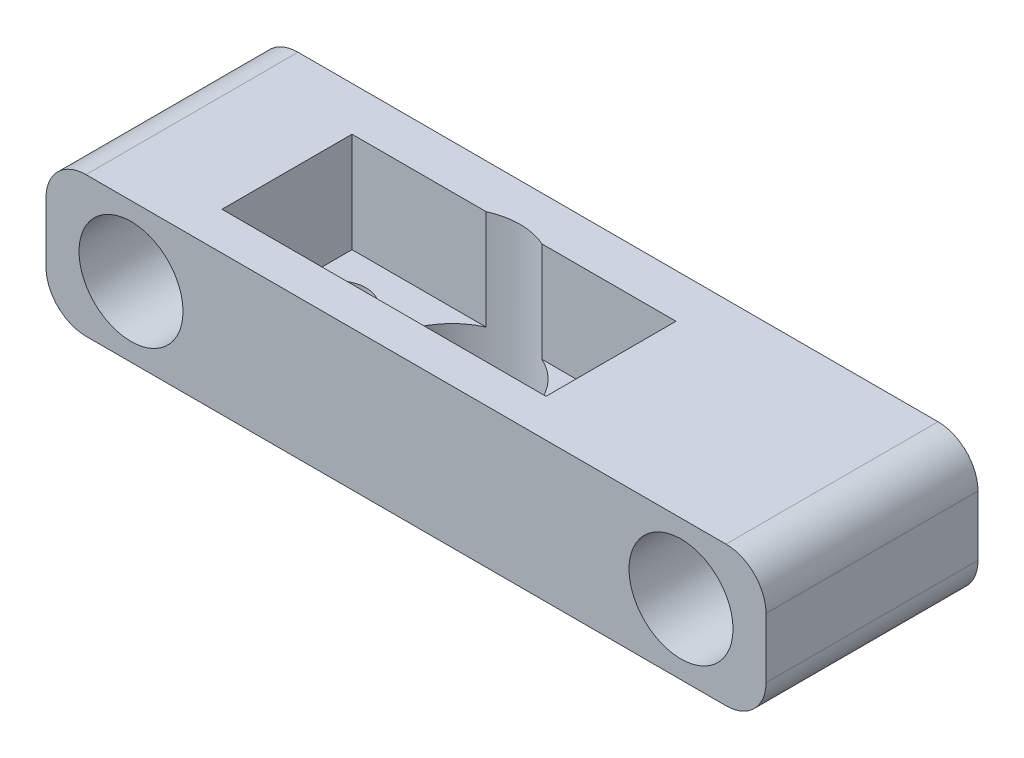
SolidWorks part; units mm, degrees
ref_plane "Alzado" through (0, 0, 0) normal (0, 0, 1) x (1, 0, 0)
ref_plane "Planta" through (0, 0, 0) normal (0, 1, 0) x (1, 0, 0)
ref_plane "Vista lateral" through (0, 0, 0) normal (1, 0, 0) x (0, 0, -1)
sketch "Croquis1" plane through (0, 0, 0) normal (0, 0, 1) x (1, 0, 0)
  line L1 (-46.0167, 15.878) -> (-10.0167, 15.878)
  line L2 (-46.0167, 15.878) -> (-46.0167, 8.878)
  line L3 (-46.0167, 8.878) -> (-10.0167, 8.878)
  line L4 (-10.0167, 15.878) -> (-10.0167, 8.878)
  circle A0 centre (-41.7667, 12.378) radius 2.6
  circle A1 centre (-14.2667, 12.378) radius 2.6
  dimension "D5" = 2
  dimension "D6" = 4.25
  dimension "D1" = 36
  dimension "D2" = 7
  dimension "D3" = 4.25
  dimension "D4" = 3.5
extrude "Saliente-Extruir1" add sketch "Croquis1" along normal blind 10.6
sketch "Croquis4" plane through (0, 8.878, 0) normal (0, -1, 0) x (1, 0, 0)
  line L0 (-35.8087, 5.3) -> (-36.8087, 5.3) construction
  line L1 (-26.2247, 5.3) -> (-28.6207, 9.45)
  line L2 (-28.6207, 9.45) -> (-33.4127, 9.45)
  line L3 (-33.4127, 9.45) -> (-35.8087, 5.3)
  line L4 (-35.8087, 5.3) -> (-33.4127, 1.15)
  line L5 (-33.4127, 1.15) -> (-28.6207, 1.15)
  line L6 (-28.6207, 1.15) -> (-26.2247, 5.3)
  line L7 (-46.0167, 10.6) -> (-46.0167, 0) construction
  line L8 (-46.0167, 10.6) -> (-10.0167, 10.6) construction
  line L9 (-10.0167, 10.6) -> (-10.0167, 0) construction
  line L10 (-46.0167, 0) -> (-10.0167, 0) construction
  circle A0 centre (-31.0167, 5.3) radius 3.25
  circle A1 centre (-31.0167, 5.3) radius 4.15 construction
  dimension "D1" = 15
  dimension "D2" = 8.3
  dimension "D3" = 1.15
sketch "Croquis5" plane through (0, 8.878, 0) normal (0, -1, 0) x (1, 0, 0)
  circle A0 centre (-31.0167, 5.3) radius 3.4
extrude "Cortar-Extruir4" cut sketch "Croquis5" against normal up to vertex (7 mm away)
fillet "Redondeo1" radius 2 4 edges at (-10.0167, 15.878, 5.3) (-10.0167, 8.878, 5.3) (-46.0167, 8.878, 5.3) (-46.0167, 15.878, 5.3)
sketch "Croquis7" plane through (0, 15.878, 0) normal (0, 1, 0) x (1, 0, 0)
  line L0 (-31.0167, -5.3) -> (-31.0167, -8.7) construction
  line L1 (-31.0167, -8.7) -> (-22.9167, -8.7) construction
  line L2 (-22.9167, -8.7) -> (-22.9167, -2.3) construction
  line L3 (-22.9167, -2.3) -> (-39.1167, -2.3) construction
  line L4 (-39.1167, -2.3) -> (-39.1167, -8.7) construction
  line L5 (-39.1167, -8.7) -> (-31.0167, -8.7) construction
  line L6 (-22.9167, -8.7) -> (-22.9167, -2.3)
  line L7 (-22.9167, -2.3) -> (-39.1167, -2.3)
  line L8 (-39.1167, -2.3) -> (-39.1167, -8.7)
  line L9 (-39.1167, -8.7) -> (-22.9167, -8.7)
  circle A0 centre (-31.0167, -5.3) radius 3.4 construction
  dimension "D1" = 16.2
  dimension "D2" = 6.4
  dimension "D3" = 8.1
extrude "Cortar-Extruir5" cut sketch "Croquis7" against normal blind 5
sketch "Croquis8" plane through (0, 10.878, 0) normal (0, 1, 0) x (1, 0, 0)
  line L0 (-22.9167, -8.7) -> (-22.9167, -2.3) construction
  line L1 (-39.1167, -2.3) -> (-39.1167, -8.7) construction
  circle A0 centre (-24.9167, -5) radius 1.5
  circle A1 centre (-37.1167, -5) radius 1.5
  dimension "D2" = 3
  dimension "D3" = 2
  dimension "D1" = 2
extrude "Cortar-Extruir6" cut sketch "Croquis8" against normal up to vertex (2 mm away)
sketch "Croquis9" plane through (0, 15.878, 0) normal (0, 1, 0) x (1, 0, 0)
  line L1 (-22.9167, -2.2) -> (-39.1167, -2.2)
  line L2 (-22.9167, -2.2) -> (-22.9167, -8.4)
  line L3 (-22.9167, -8.4) -> (-39.1167, -8.4)
  line L4 (-39.1167, -2.2) -> (-39.1167, -8.4)
  line L5 (-22.9167, -2.2) -> (-39.1167, -8.4) construction
  line L6 (-22.9167, -8.4) -> (-39.1167, -2.2) construction
  point P0 (-31.0167, -5.3)
  dimension "D1" = 6.2
  dimension "D2" = 16.2
extrude "Cortar-Extruir7" cut sketch "Croquis9" against normal up to vertex (5 mm away)
